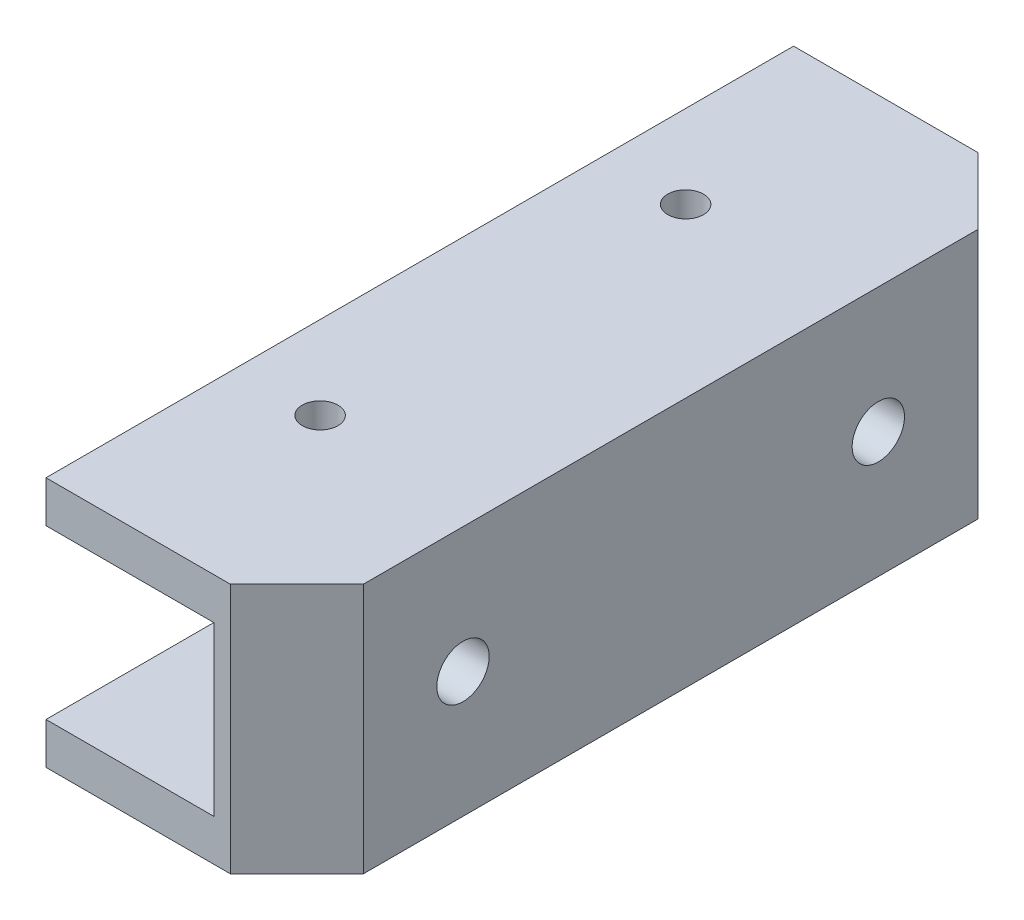
SolidWorks part; units mm, degrees
ref_plane "前视基准面" through (0, 0, 0) normal (0, 0, 1) x (1, 0, 0)
ref_plane "上视基准面" through (0, 0, 0) normal (0, 1, 0) x (1, 0, 0)
ref_plane "右视基准面" through (0, 0, 0) normal (1, 0, 0) x (0, 0, -1)
sketch "草图1" plane through (0, 0, 0) normal (0, 0, 1) x (1, 0, 0)
  line L0 (0, 0) -> (0, -5)
  line L1 (0, 0) -> (20.2, 0)
  line L3 (0, 20.2) -> (20.2, 20.2)
  line L4 (20.2, 0) -> (20.2, 20.2)
  line L5 (0, 25.2) -> (25.2, 25.2)
  line L6 (0, 25.2) -> (0, 20.2)
  line L7 (0, -5) -> (25.2, -5)
  line L8 (25.2, 25.2) -> (25.2, -5)
  dimension "D1" = 20.2
  dimension "D2" = 20.2
  dimension "D3" = 5
  dimension "D4" = 5
  dimension "D5" = 5
extrude "凸台-拉伸1" add sketch "草图1" along normal blind 60
sketch "草图2" plane through (0, 25.2, 0) normal (0, 1, 0) x (1, 0, 0)
  line L0 (10, 9.0589) -> (10, -69.7863) construction
  line L1 (0, -60) -> (0, 0) construction
  line L2 (0, -29.7663) -> (45.4732, -29.7663) construction
  line L3 (0, -14.6663) -> (20, -14.6663)
  line L4 (0, -14.6663) -> (0, -24.6663)
  line L5 (0, -24.6663) -> (20, -24.6663)
  line L6 (20, -14.6663) -> (20, -24.6663)
  line L7 (0, -34.8663) -> (20, -34.8663)
  line L8 (0, -34.8663) -> (0, -44.8663)
  line L9 (0, -44.8663) -> (20, -44.8663)
  line L10 (20, -34.8663) -> (20, -44.8663)
  dimension "D1" = 10
  dimension "D2" = 20
  dimension "D3" = 20
  dimension "D4" = 10
  dimension "D5" = 10
  dimension "D6" = 10.2
  dimension "D7" = 5.1
extrude "凸台-拉伸2" [suppressed] add sketch "草图2" along normal blind 20
sketch "草图3" [suppressed] plane through (0, 25.2, 0) normal (0, 1, 0) x (1, 0, 0)
  line L0 (20, -34.8663) -> (0, -34.8663) construction
  line L1 (0, -24.6663) -> (3.9, -24.6663)
  line L2 (0, -24.6663) -> (0, -34.8663)
  line L3 (0, -34.8663) -> (3.9, -34.8663)
  line L4 (3.9, -24.6663) -> (3.9, -34.8663)
  line L5 (20, -34.8663) -> (0, -34.8663) construction
  line L6 (20, -24.6663) -> (16.1, -24.6663)
  line L7 (20, -24.6663) -> (20, -34.8663)
  line L8 (20, -34.8663) -> (16.1, -34.8663)
  line L9 (16.1, -24.6663) -> (16.1, -34.8663)
  dimension "D1" = 3.9
  dimension "D2" = 12.2
  dimension "D3" = 3.9
extrude "凸台-拉伸3" [suppressed] add sketch "草图3" along normal blind 10
chamfer "倒角1" [suppressed] distance 3.9 angle 45
chamfer "倒角2" [suppressed] distance 15 angle 45
sketch "草图4" plane through (0, 25.2, 0) normal (0, 1, 0) x (1, 0, 0)
  line L0 (0, -60) -> (0, 0) construction
  line L1 (0, -60) -> (0, 0) construction
  line L2 (25.2, 0) -> (0, 0) construction
  line L3 (25.2, -60) -> (0, -60) construction
  circle A0 centre (10, -8) radius 2.15
  circle A1 centre (10, -52) radius 2.15
  dimension "D1" = 10
  dimension "D2" = 10
  dimension "D3" = 4.3
  dimension "D4" = 4.3
  dimension "D5" = 8
  dimension "D6" = 8
extrude "切除-拉伸1" cut sketch "草图4" against normal blind 40
sketch "草图5" plane through (25.2, 0, 0) normal (1, 0, 0) x (0, 0, -1)
  line L0 (-60, 25.2) -> (0, 25.2) construction
  line L2 (0, -5) -> (0, 25.2) construction
  line L3 (-60, -5) -> (-60, 25.2) construction
  circle A0 centre (-55, 10.1) radius 3.15
  circle A1 centre (-5, 10.1) radius 3.15
  dimension "D1" = 6.3
  dimension "D2" = 15.1
  dimension "D3" = 5
  dimension "D4" = 15.1
  dimension "D5" = 5
  dimension "D6" = 6.3
extrude "切除-拉伸2" cut sketch "草图5" against normal blind 40
sketch "草图6" [suppressed] plane through (0, 0, 44.8663) normal (0, 0, 1) x (1, 0, 0)
  line L0 (0, 45.2) -> (20, 45.2) construction
  line L1 (0, 25.2) -> (20, 25.2) construction
  circle A0 centre (10, 40.2) radius 1.6
  circle A1 centre (10, 30.2) radius 1.6
  dimension "D1" = 3.2
  dimension "D2" = 3.2
  dimension "D3" = 5
  dimension "D4" = 5
extrude "切除-拉伸3" [suppressed] cut sketch "草图6" against normal blind 36
chamfer "倒角3" [suppressed] distance 1.5 angle 45
sketch "草图7" plane through (0, 0, 60) normal (0, 0, 1) x (1, 0, 0)
  line L8 (20.2, 0) -> (0, 0)
  line L9 (0, 0) -> (0, -5)
  line L10 (0, -5) -> (25.2, -5)
  line L11 (25.2, -5) -> (25.2, 25.2)
  line L12 (25.2, 25.2) -> (0, 25.2)
  line L13 (0, 25.2) -> (0, 20.2)
  line L14 (0, 20.2) -> (20.2, 20.2)
  line L15 (20.2, 20.2) -> (20.2, 0)
  line L16 (20.2, 0) -> (0, 0)
  line L17 (0, 0) -> (0, -5)
  line L18 (0, -5) -> (25.2, -5)
  line L19 (25.2, -5) -> (25.2, 25.2)
  line L20 (25.2, 25.2) -> (0, 25.2)
  line L21 (0, 25.2) -> (0, 20.2)
  line L22 (0, 20.2) -> (20.2, 20.2)
  line L23 (20.2, 20.2) -> (20.2, 0)
  dimension "D1" = 0
extrude "凸台-拉伸4" [suppressed] add sketch "草图7" along normal blind 25
fillet "圆角1" [suppressed] radius 10
sketch "草图8" [suppressed] plane through (25.2, 0, 0) normal (1, 0, 0) x (0, 0, -1)
  line L0 (-85, -5) -> (0, -5) construction
  line L1 (-85, 25.2) -> (-80, 25.2)
  line L2 (-85, 25.2) -> (-85, -5)
  line L3 (-85, -5) -> (-80, -5)
  line L4 (-80, 25.2) -> (-80, -5)
  line L5 (-85, 25.2) -> (0, 25.2) construction
  line L6 (-59.8, 25.2) -> (-54.8, 25.2)
  line L7 (-59.8, 25.2) -> (-59.8, -5)
  line L8 (-59.8, -5) -> (-54.8, -5)
  line L9 (-54.8, 25.2) -> (-54.8, -5)
  dimension "D1" = 5
  dimension "D2" = 5
  dimension "D3" = 20.2
extrude "凸台-拉伸5" [suppressed] add sketch "草图8" along normal blind 20
chamfer "倒角4" [suppressed] distance 5 angle 45
sketch "草图9" [suppressed] plane through (0, 0, 85) normal (0, 0, 1) x (1, 0, 0)
  line L0 (45.2, 25.2) -> (45.2, -5) construction
  line L1 (45.2, 25.2) -> (20.2, 25.2) construction
  line L2 (0, -5) -> (45.2, -5) construction
  circle A0 centre (35.2, 17.2) radius 2.15
  circle A1 centre (35.2, 3) radius 2.15
  dimension "D1" = 4.3
  dimension "D2" = 4.3
  dimension "D3" = 10
  dimension "D4" = 10
  dimension "D5" = 8
  dimension "D6" = 8
extrude "切除-拉伸4" [suppressed] cut sketch "草图9" against normal blind 46
chamfer "倒角5" [suppressed] distance 1 angle 45
sketch "草图10" plane through (0, 0, 0) normal (0, 0, -1) x (-1, 0, 0)
  line L6 (-20.2, 20.2) -> (0, 20.2)
  line L8 (0, 0) -> (-20.2, 0)
  line L9 (-20.2, 0) -> (-20.2, 20.2)
  line L13 (-20.2, 20.2) -> (0, 20.2)
  line L14 (-25.2, -5) -> (0, -5)
  line L15 (0, -5) -> (0, 0)
  line L16 (0, 0) -> (-20.2, 0)
  line L17 (-20.2, 0) -> (-20.2, 20.2)
  line L22 (-25.2, -5) -> (0, -5)
  line L23 (0, -5) -> (0, 0)
  line L30 (0, 20.2) -> (0, 25.2)
  line L31 (0, 20.2) -> (0, 25.2)
  line L32 (0, 25.2) -> (-25.2, 25.2)
  line L33 (0, 25.2) -> (-25.2, 25.2)
  line L34 (-25.2, 25.2) -> (-25.2, -5)
  line L35 (-25.2, 25.2) -> (-25.2, -5)
  dimension "D1" = 0
extrude "凸台-拉伸6" add sketch "草图10" along normal blind 15
sketch "草图11" plane through (0, 0, 60) normal (0, 0, 1) x (1, 0, 0)
  line L8 (20.2, 0) -> (0, 0)
  line L9 (0, 0) -> (0, -5)
  line L10 (0, -5) -> (25.2, -5)
  line L11 (25.2, -5) -> (25.2, 25.2)
  line L12 (25.2, 25.2) -> (0, 25.2)
  line L13 (0, 25.2) -> (0, 20.2)
  line L14 (0, 20.2) -> (20.2, 20.2)
  line L15 (20.2, 20.2) -> (20.2, 0)
  line L16 (20.2, 0) -> (0, 0)
  line L17 (0, 0) -> (0, -5)
  line L18 (0, -5) -> (25.2, -5)
  line L19 (25.2, -5) -> (25.2, 25.2)
  line L20 (25.2, 25.2) -> (0, 25.2)
  line L21 (0, 25.2) -> (0, 20.2)
  line L22 (0, 20.2) -> (20.2, 20.2)
  line L23 (20.2, 20.2) -> (20.2, 0)
  dimension "D1" = 0
extrude "凸台-拉伸7" add sketch "草图11" along normal blind 15
sketch "草图12" plane through (25.2, 0, 0) normal (1, 0, 0) x (0, 0, -1)
  line L4 (-75, -5) -> (15, -5)
  line L5 (15, -5) -> (15, 25.2)
  line L6 (15, 25.2) -> (-75, 25.2)
  line L7 (-75, 25.2) -> (-75, -5)
  line L8 (-75, -5) -> (15, -5)
  line L10 (15, 25.2) -> (-75, 25.2)
  line L11 (-75, 25.2) -> (-75, -5)
  line L13 (15, -5) -> (15, 25.2)
  circle A0 centre (-55, 10.1) radius 3.15 construction
  circle A1 centre (-55, 10.1) radius 3.15
  circle A2 centre (-5, 10.1) radius 3.15 construction
  circle A3 centre (-5, 10.1) radius 3.15
  dimension "D1" = 0
extrude "凸台-拉伸8" add sketch "草图12" along normal blind 5
chamfer "倒角6" distance 8 angle 45 2 edges at (30.2, 10.1, 75) (30.2, 10.1, -15)
sketch "草图13" plane through (20.2, 0, 0) normal (-1, 0, 0) x (0, 0, 1)
  circle A0 centre (5, 10.1) radius 7.5
  circle A1 centre (55, 10.1) radius 7.5
  dimension "D1" = 15
  dimension "D2" = 15
extrude "切除-拉伸5" cut sketch "草图13" against normal blind 5
